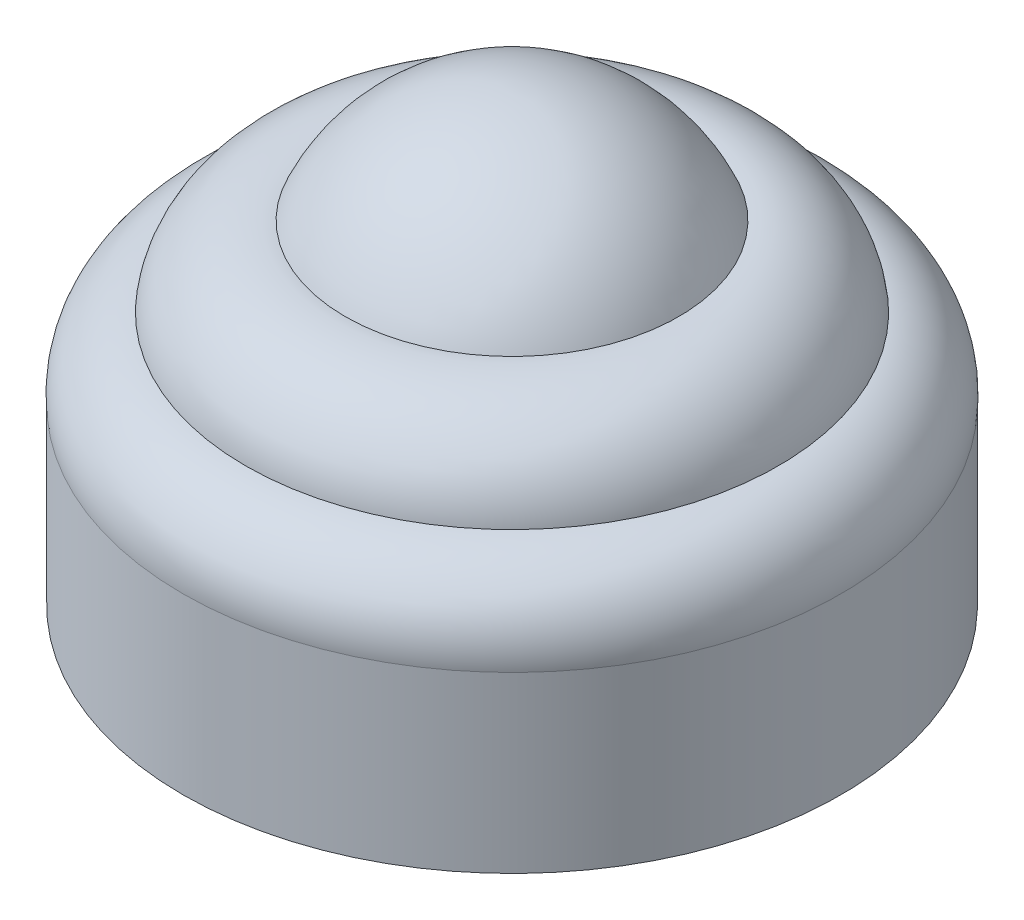
SolidWorks part; units mm, degrees
ref_plane "정면" through (0, 0, 0) normal (0, 0, 1) x (1, 0, 0)
ref_plane "윗면" through (0, 0, 0) normal (0, 1, 0) x (1, 0, 0)
ref_plane "우측면" through (0, 0, 0) normal (1, 0, 0) x (0, 0, -1)
sketch "스케치1" plane through (0, 0, 0) normal (1, 0, 0) x (0, 0, -1)
  line L0 (7.9989, 11.3633) -> (54.9989, 11.3633) construction
  line L1 (31.6904, 27.6549) -> (31.6904, 18.5122) construction
  line L2 (17.1973, 20.6551) -> (17.1973, 12.9899)
  line L3 (17.1973, 12.9899) -> (31.6904, 12.9899)
  line L5 (31.6904, 12.9899) -> (31.6904, 32.4899)
  arc A1 (31.6904, 32.4899) -> (24.3431, 27.6549) centre (31.6904, 24.4899) ccw
  arc A2 (24.3431, 27.6549) -> (19.9606, 24.1515) centre (23.9035, 23.7119) ccw
  arc A3 (19.9606, 24.1515) -> (17.1973, 20.6551) centre (20.3271, 21.0217) ccw
  point P19 (31.6904, 12.9899)
  dimension "D2" = 16
  dimension "D1" = 47
revolve "회전2" add sketch "스케치1" angle 360 about L1
